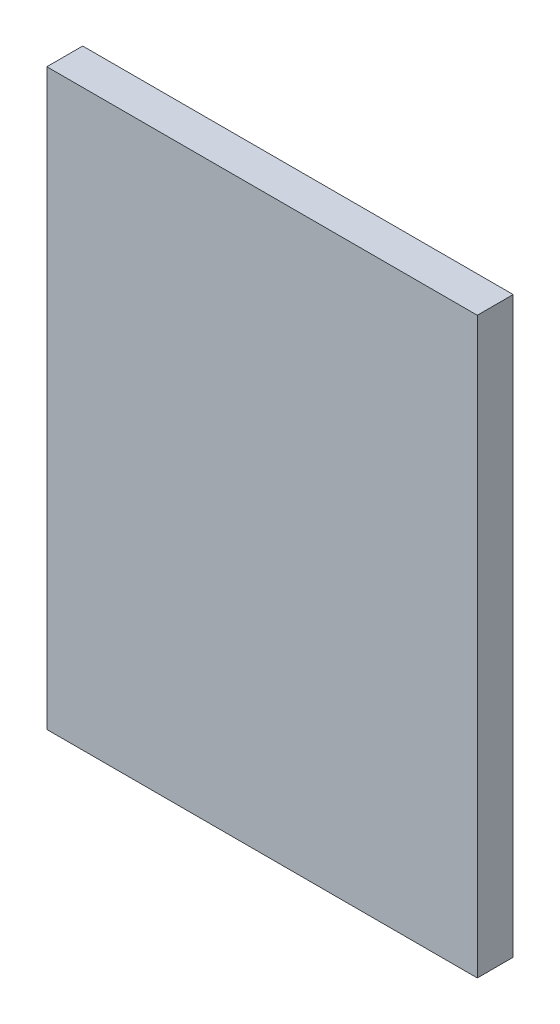
SolidWorks part; units mm, degrees
ref_plane "Front" through (0, 0, 0) normal (0, 0, 1) x (1, 0, 0)
ref_plane "Top" through (0, 0, 0) normal (0, 1, 0) x (1, 0, 0)
ref_plane "Right" through (0, 0, 0) normal (1, 0, 0) x (0, 0, -1)
sketch "Sketch1" plane through (0, 0, 0) normal (0, 0, 1) x (1, 0, 0)
  line L1 (-914.4, -1219.2) -> (914.4, -1219.2)
  line L2 (-914.4, -1219.2) -> (-914.4, 1219.2)
  line L3 (-914.4, 1219.2) -> (914.4, 1219.2)
  line L4 (914.4, -1219.2) -> (914.4, 1219.2)
  line L5 (-914.4, -1219.2) -> (914.4, 1219.2) construction
  line L6 (-914.4, 1219.2) -> (914.4, -1219.2) construction
  point P0 (0, 0)
  dimension "D1" = 1828.8
  dimension "D2" = 2438.4
extrude "Boss-Extrude1" add sketch "Sketch1" along normal blind 152.4
equation "\"width\"=72"
equation "\"D1@Sketch1\"=\"width\""
equation "\"height\"=96"
equation "\"D2@Sketch1\"=\"height\""
equation "\"wall\"=6"
equation "\"D1@Boss-Extrude1\"=\"wall\""
